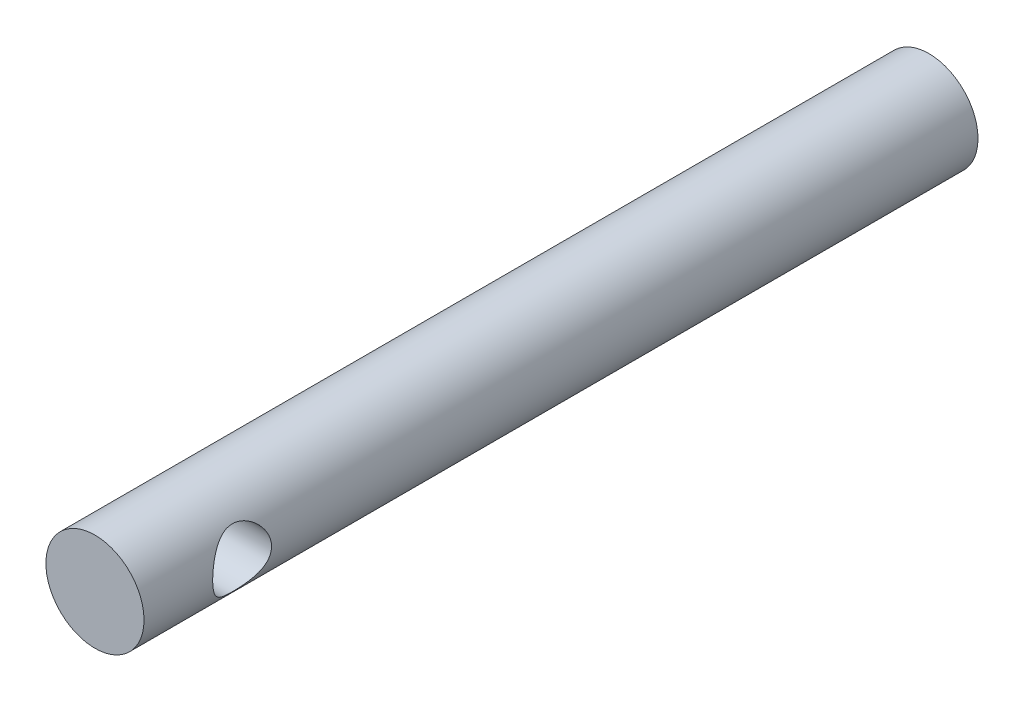
SolidWorks part; units mm, degrees
ref_plane "Alzado" through (0, 0, 0) normal (0, 0, 1) x (1, 0, 0)
ref_plane "Planta" through (0, 0, 0) normal (0, 1, 0) x (1, 0, 0)
ref_plane "Vista lateral" through (0, 0, 0) normal (1, 0, 0) x (0, 0, -1)
sketch "Croquis1" plane through (0, 0, 0) normal (0, 0, 1) x (1, 0, 0)
  circle A0 centre (0, 0) radius 2.5
  dimension "D1" = 5
extrude "Saliente-Extruir1" add sketch "Croquis1" along normal blind 42.5
sketch "Croquis2" plane through (0, 0, 0) normal (1, 0, 0) x (0, 0, -1)
  line L0 (-42.5, 2.5) -> (-42.5, -2.5) construction
  circle A0 centre (-37.5, 0) radius 1.5
  dimension "D1" = 3
  dimension "D2" = 5
extrude "Cortar-Extruir1" cut sketch "Croquis2" against normal mid plane 50
